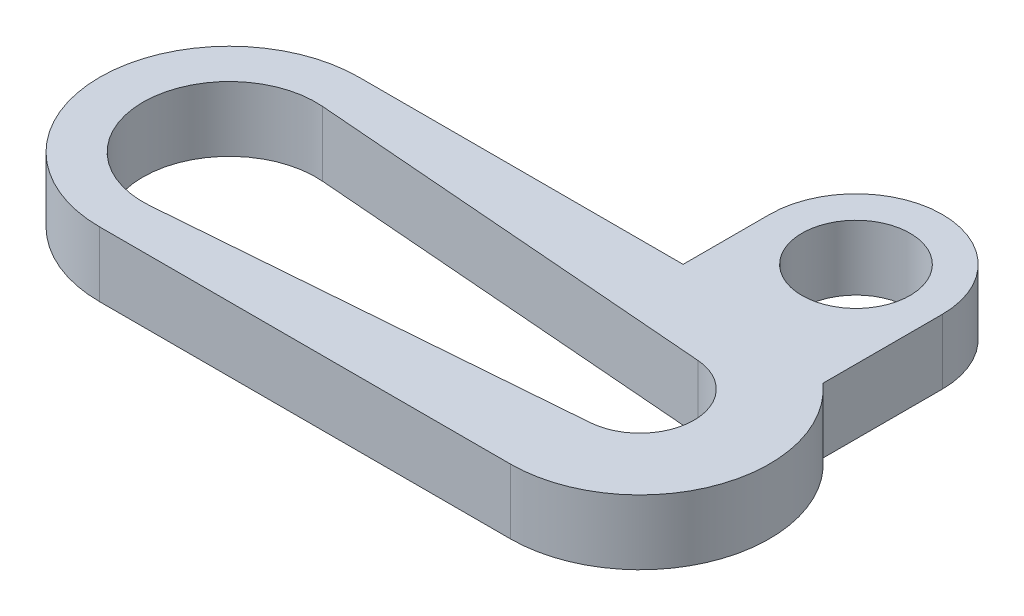
SolidWorks part; units mm, degrees
ref_plane "前视基准面" through (0, 0, 0) normal (0, 0, 1) x (1, 0, 0)
ref_plane "上视基准面" through (0, 0, 0) normal (0, 1, 0) x (1, 0, 0)
ref_plane "右视基准面" through (0, 0, 0) normal (1, 0, 0) x (0, 0, -1)
sketch "草图1" plane through (0, 0, 0) normal (0, 1, 0) x (1, 0, 0)
  line L0 (0, 0) -> (19, 0) construction
  line L1 (0.3158, 3.9875) -> (19.1974, 2.4922)
  line L2 (19.1974, -2.4922) -> (0.3158, -3.9875)
  line L3 (0, 0) -> (-4, 0) construction
  line L4 (19, 0) -> (21.5, 0) construction
  line L5 (19, 6) -> (0, 6)
  line L6 (0, -6) -> (19, -6)
  line L7 (19, 0) -> (19, 10) construction
  line L8 (15, 10) -> (15, 6)
  line L9 (23, 10) -> (23, 4.4721)
  circle A0 centre (0, 0) radius 4
  circle A1 centre (19, 0) radius 2.5
  circle A2 centre (0, 0) radius 6
  circle A3 centre (19, 0) radius 6
  circle A4 centre (19, 10) radius 4
  circle A5 centre (19, 10) radius 2.5
  dimension "D1" = 8
  dimension "D2" = 5
  dimension "D3" = 25.5
  dimension "D4" = 12
  dimension "D5" = 12
  dimension "D7" = 5
  dimension "D8" = 8
  dimension "D6" = 10
extrude "凸台-拉伸1" add sketch "草图1" along normal blind 3 contours A2 L2 A0 L1 | A3 L5 A2 L1 | A3 L2 A2 L6 | A3 L1 A1 L2 | A4 L8 L5 | A4 A5 | A4 A3 L9
